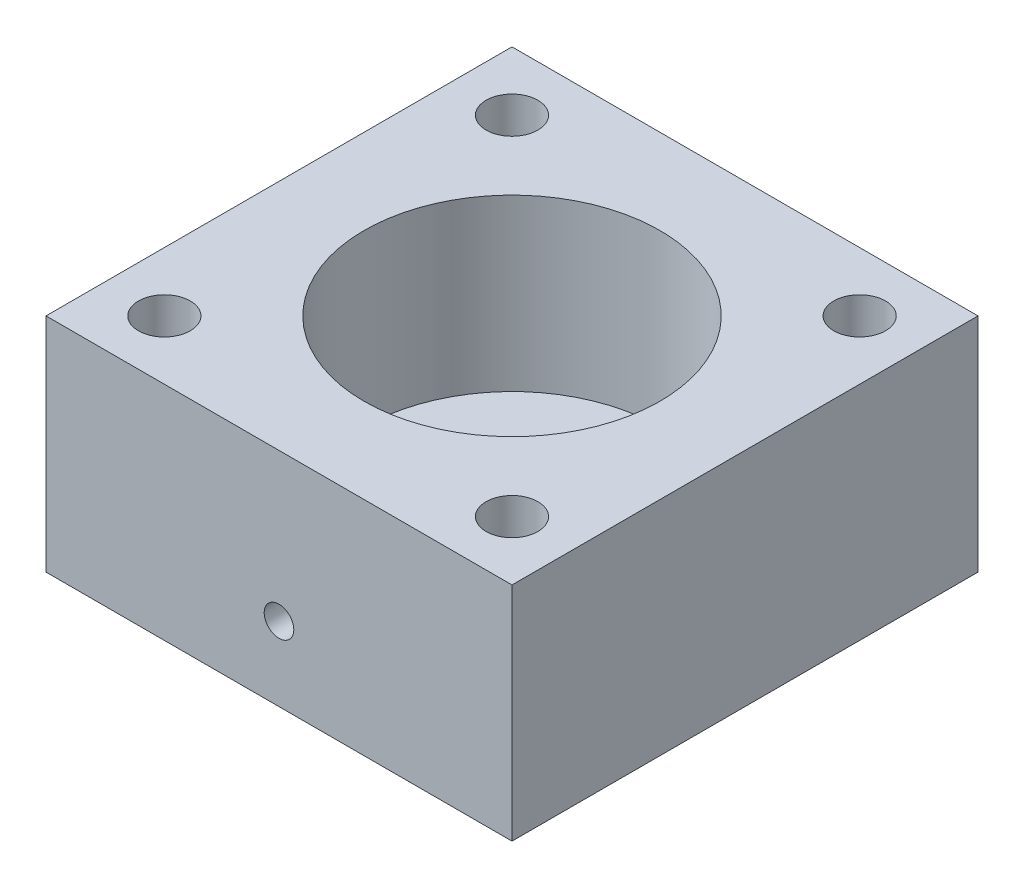
SolidWorks part; units mm, degrees
ref_plane "Alzado" through (0, 0, 0) normal (0, 0, 1) x (1, 0, 0)
ref_plane "Planta" through (0, 0, 0) normal (0, 1, 0) x (1, 0, 0)
ref_plane "Vista lateral" through (0, 0, 0) normal (1, 0, 0) x (0, 0, -1)
sketch "Croquis1" plane through (0, 0, 0) normal (0, 1, 0) x (1, 0, 0)
  line L1 (-15.75, -15.75) -> (15.75, -15.75)
  line L2 (-15.75, -15.75) -> (-15.75, 15.75)
  line L3 (-15.75, 15.75) -> (15.75, 15.75)
  line L4 (15.75, -15.75) -> (15.75, 15.75)
  line L5 (-15.75, -15.75) -> (15.75, 15.75) construction
  line L6 (-15.75, 15.75) -> (15.75, -15.75) construction
  point P0 (0, 0)
  dimension "D1" = 31.5
  dimension "D2" = 31.5
extrude "Saliente-Extruir1" add sketch "Croquis1" along normal blind 15 contours L3 L4 L1 L2
sketch "Croquis3" plane through (0, 15, 0) normal (0, 1, 0) x (1, 0, 0)
  circle A0 centre (0, 0) radius 10
  dimension "D2" = 20
extrude "Cortar-Extruir1" cut sketch "Croquis3" against normal blind 11.5
sketch "Croquis6" plane through (0, 15, 0) normal (0, 1, 0) x (1, 0, 0)
  line L0 (-15.75, -15.75) -> (15.75, -15.75) construction
  line L1 (-15.75, -15.75) -> (-15.75, 15.75) construction
  line L2 (0, -15.75) -> (0, 15.75) construction
  line L3 (-15.75, 15.75) -> (15.75, 15.75) construction
  line L4 (-15.75, 0) -> (15.75, 0) construction
  line L5 (15.75, -15.75) -> (15.75, 15.75) construction
  circle A0 centre (-11.75, -11.75) radius 1.75
  circle A1 centre (11.75, -11.75) radius 1.75
  circle A2 centre (11.75, 11.75) radius 1.75
  circle A3 centre (-11.75, 11.75) radius 1.75
  dimension "D1" = 3.5
  dimension "D2" = 4
  dimension "D3" = 4
extrude "Cortar-Extruir2" cut sketch "Croquis6" against normal through all
sketch "Croquis7" plane through (0, 0, 15.75) normal (0, 0, 1) x (1, 0, 0)
  line L0 (-15.75, 0) -> (15.75, 0) construction
  circle A0 centre (0, 5) radius 1
  dimension "D1" = 5
  dimension "D2" = 2
extrude "Cortar-Extruir3" cut sketch "Croquis7" against normal up to surface (5.8001 mm away) contours A0
